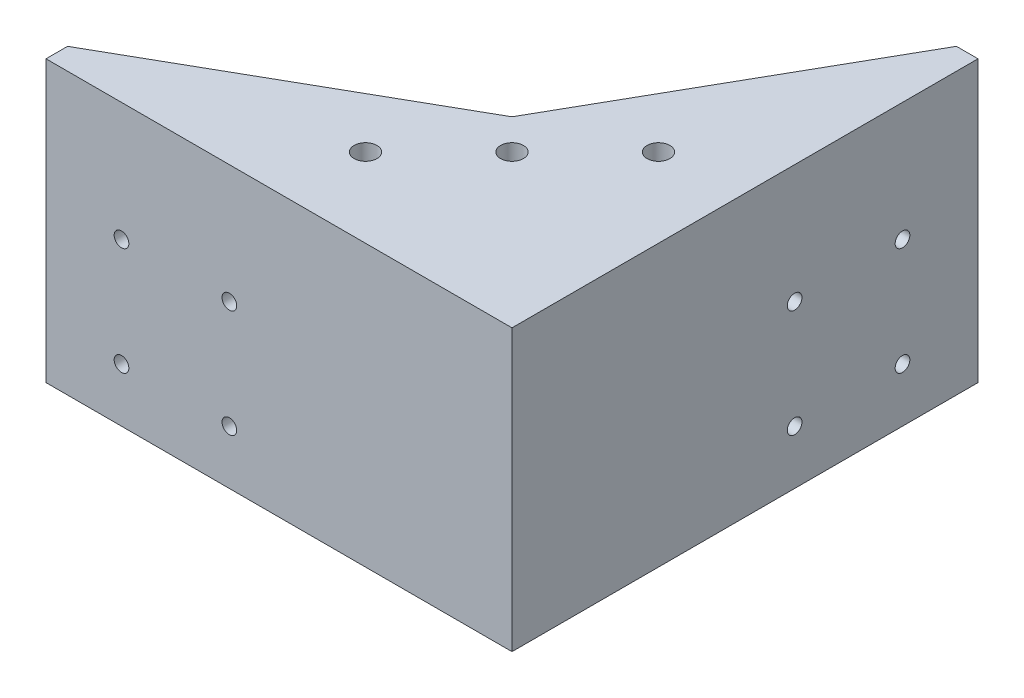
SolidWorks part; units mm, degrees
ref_plane "前视基准面" through (0, 0, 0) normal (0, 0, 1) x (1, 0, 0)
ref_plane "上视基准面" through (0, 0, 0) normal (0, 1, 0) x (1, 0, 0)
ref_plane "右视基准面" through (0, 0, 0) normal (1, 0, 0) x (0, 0, -1)
other "Configuration Table"
sketch "草图3" plane through (0, 0, 0) normal (0, 1, 0) x (1, 0, 0)
  line L1 (-54, 54) -> (54, 54)
  line L2 (-54, 54) -> (-54, -54)
  line L3 (-54, -54) -> (54, -54)
  line L4 (54, 54) -> (54, -54)
  line L5 (-54, 54) -> (54, -54) construction
  line L6 (-54, -54) -> (54, 54) construction
  line L7 (-54, 54) -> (49, 54)
  line L8 (-54, 54) -> (-54, -49)
  line L9 (-54, -49) -> (49, -49)
  line L10 (49, 54) -> (49, -49)
  point P0 (0, 0)
  dimension "D1" = 108
  dimension "D2" = 108
  dimension "D3" = 103
extrude "凸台-拉伸2" add sketch "草图3" along normal blind 60 contours L1 L10 L9 L2 L3 L4
sketch "草图4" plane through (0, 0, 49) normal (0, 0, -1) x (-1, 0, 0)
  line L0 (24, 60) -> (24, 0) construction
  line L1 (54, 60) -> (-49, 60) construction
  line L2 (54, 0) -> (-49, 0) construction
  line L3 (-49, 60) -> (-49, 0) construction
  line L4 (-49, 25) -> (54, 25) construction
  circle A0 centre (36.5, 37.5) radius 1.7
  circle A1 centre (36.5, 12.5) radius 1.7
  circle A2 centre (11.5, 12.5) radius 1.7
  circle A3 centre (11.5, 37.5) radius 1.7
  dimension "D4" = 3.4
  dimension "D1" = 73
  dimension "D2" = 25
  dimension "D3" = 25
  dimension "D5" = 35
sketch "草图5" plane through (49, 0, 0) normal (-1, 0, 0) x (0, 0, 1)
  line L0 (-54, 25) -> (49, 25) construction
  line L2 (49, 60) -> (49, 0) construction
  line L3 (-24, 60) -> (-24, 0) construction
  line L4 (-54, 60) -> (49, 60) construction
  line L5 (-54, 0) -> (49, 0) construction
  circle A0 centre (-36.5, 37.5) radius 1.7
  circle A1 centre (-36.5, 12.5) radius 1.7
  circle A2 centre (-11.5, 12.5) radius 1.7
  circle A3 centre (-11.5, 37.5) radius 1.7
  dimension "D4" = 3.4
  dimension "D1" = 73
  dimension "D2" = 25
  dimension "D3" = 25
  dimension "D5" = 35
extrude "切除-拉伸1" cut sketch "草图4" against normal through all
extrude "切除-拉伸2" cut sketch "草图5" against normal through all
sketch "草图6" plane through (0, 60, 0) normal (0, 1, 0) x (1, 0, 0)
  line L0 (-54, -49) -> (49, 54) construction
  line L1 (-54, -49) -> (-54, -54)
  line L2 (-54, -54) -> (54, -54)
  line L3 (54, -54) -> (54, 54)
  line L4 (54, 54) -> (49, 54)
  line L5 (54, 16.5736) -> (-16.5736, -54) construction
  line L6 (54, 54) -> (54, -54) construction
  line L7 (54, -54) -> (-2.5, 2.5) construction
  line L8 (-54, -49) -> (11.6421, -11.6421)
  line L9 (11.6421, -11.6421) -> (49, 54)
  circle A0 centre (1.7426, -35.6838) radius 2.65
  circle A1 centre (35.6838, -1.7426) radius 2.65
  circle A2 centre (18.7132, -18.7132) radius 2.65
  dimension "D2" = 5.3
  dimension "D1" = 30
  dimension "D3" = 24
  dimension "D4" = 20
extrude "凸台-拉伸4" add sketch "草图6" along normal blind 5
ref_plane "基准面1" through (0, 0, 14) normal (0, 0, -1) x (-1, 0, 0)
sketch "草图10" plane through (0, 0, 14) normal (0, 0, -1) x (-1, 0, 0)
  line L0 (-30.3211, 60) -> (-49, 40)
  line L1 (-49, 60) -> (-11.6421, 60) construction
  line L2 (-49, 60) -> (-49, 0) construction
  line L3 (54, 60) -> (-49, 60) construction
  dimension "D1" = 20
rib "筋1" sketch "草图10" sketch "草图10" thickness 35 extrusion direction parallel to sketch draft on no parameters "D1"=35
ref_plane "基准面2" through (14, 0, 0) normal (-1, 0, 0) x (0, 0, 1)
sketch "草图13" plane through (14, 0, 0) normal (-1, 0, 0) x (0, 0, 1)
  line L0 (29, 60) -> (49, 40)
  line L1 (14, 60) -> (49, 60) construction
  line L2 (49, 40) -> (49, 0) construction
  line L3 (14, 60) -> (49, 60) construction
  dimension "D1" = 20
  dimension "D2" = 20
rib "筋4" sketch "草图13" sketch "草图13" thickness 35 extrusion direction parallel to sketch draft on no parameters "D1"=35
